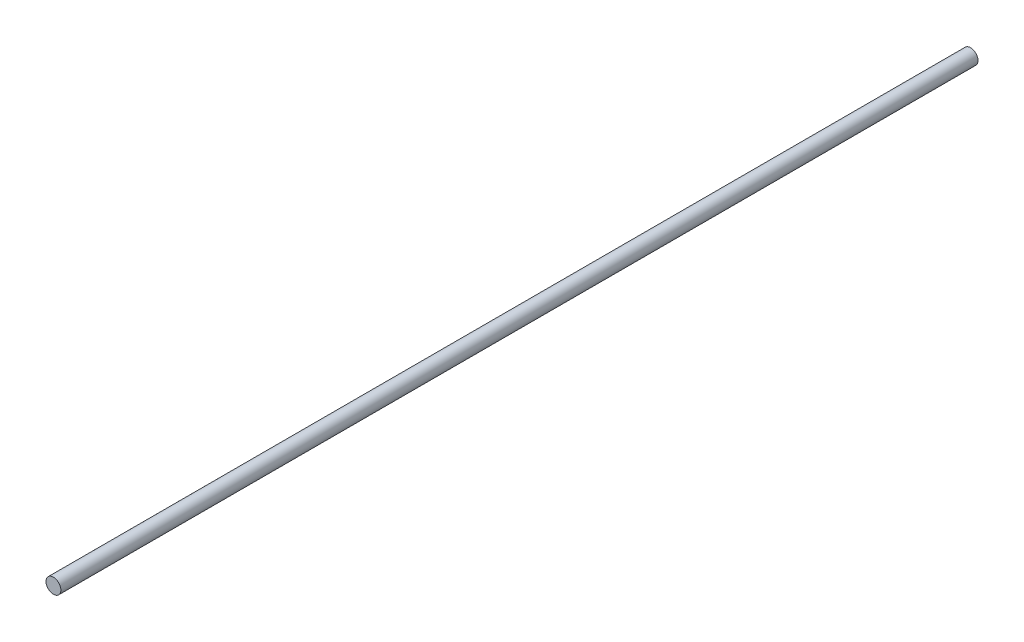
SolidWorks part; units mm, degrees
ref_plane "Front Plane" through (0, 0, 0) normal (0, 0, 1) x (1, 0, 0)
ref_plane "Top Plane" through (0, 0, 0) normal (0, 1, 0) x (1, 0, 0)
ref_plane "Right Plane" through (0, 0, 0) normal (1, 0, 0) x (0, 0, -1)
sketch "Sketch1" plane through (0, 0, 0) normal (0, 0, 1) x (1, 0, 0)
  circle A0 centre (-32.4095, 8.4317) radius 3
extrude "Boss-Extrude1" add sketch "Sketch1" along normal blind 370
